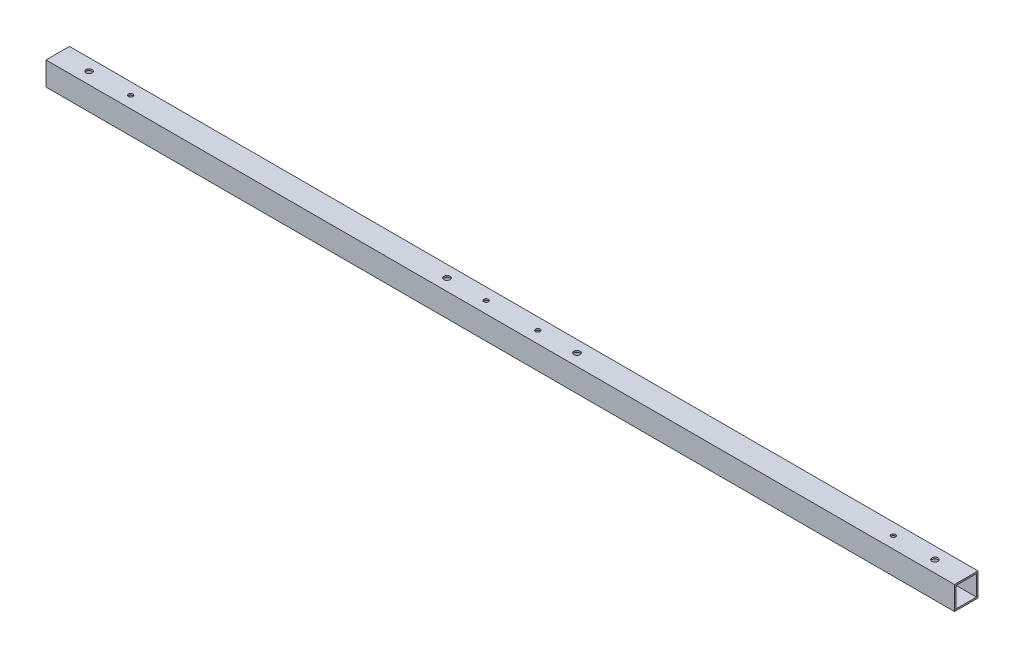
SolidWorks part; units mm, degrees
material "1060 合金"
ref_plane "前视基准面" through (0, 0, 0) normal (0, 0, 1) x (1, 0, 0)
ref_plane "上视基准面" through (0, 0, 0) normal (0, 1, 0) x (1, 0, 0)
ref_plane "右视基准面" through (0, 0, 0) normal (1, 0, 0) x (0, 0, -1)
other "Configuration Table"
sketch "草图1" plane through (0, 0, 0) normal (0, 1, 0) x (1, 0, 0)
  line L0 (-320, 0) -> (320, 0)
  dimension "D1" = 640
other "铝管 15X15X1(1)"
ref_plane "基准面1" through (-320, 0, 0) normal (1, 0, 0) x (0, 0, -1)
sketch "草图11" plane through (-320, 0, 0) normal (1, 0, 0) x (0, 0, -1)
  line L1 (-7.5, -7.5) -> (7.5, -7.5)
  line L2 (-7.5, -7.5) -> (-7.5, 7.5)
  line L3 (-7.5, 7.5) -> (7.5, 7.5)
  line L4 (7.5, -7.5) -> (7.5, 7.5)
  line L5 (-7.5, -7.5) -> (7.5, 7.5) construction
  line L6 (-7.5, 7.5) -> (7.5, -7.5) construction
  line L7 (-6.5, -6.5) -> (6.5, -6.5)
  line L8 (-6.5, -6.5) -> (-6.5, 6.5)
  line L9 (-6.5, 6.5) -> (6.5, 6.5)
  line L10 (6.5, -6.5) -> (6.5, 6.5)
  line L11 (-6.5, -6.5) -> (6.5, 6.5) construction
  line L12 (-6.5, 6.5) -> (6.5, -6.5) construction
  point P0 (0, 0)
  point P6 (0, 0)
  point P11 (0, 0)
  dimension "D1" = 15
  dimension "D2" = 15
  dimension "D3" = 13
  dimension "D4" = 13
sketch "草图12" plane through (0, 7.5, 0) normal (0, 1, 0) x (1, 0, 0)
  line L0 (-320, 0) -> (320, 0) construction
  line L2 (0, 7.5) -> (0, -7.5) construction
  line L3 (320, 7.5) -> (-320, 7.5) construction
  line L4 (320, -7.5) -> (-320, -7.5) construction
  line L5 (-320, 7.5) -> (-320, -7.5) construction
  circle A0 centre (-41.5, 0) radius 1.95
  circle A1 centre (-270, 0) radius 1.95
  circle A2 centre (270, 0) radius 1.95
  circle A3 centre (41.5, 0) radius 1.95
  dimension "D1" = 3.9
  dimension "D2" = 3.9
  dimension "D4" = 41.5
  dimension "D3" = 50
extrude "切除-拉伸1" cut sketch "草图12" against normal through all
sketch "草图13" plane through (0, 7.5, 0) normal (0, 1, 0) x (1, 0, 0)
  line L0 (-320, 0) -> (320, 0) construction
  line L1 (-320, 7.5) -> (-320, -7.5) construction
  line L2 (0, 7.5) -> (0, -9.1662) construction
  line L3 (320, 7.5) -> (-320, 7.5) construction
  circle A0 centre (-243.5, 0) radius 1.45
  circle A1 centre (243.5, 0) radius 1.45
  dimension "D1" = 2.9
  dimension "D2" = 76.5
extrude "切除-拉伸2" cut sketch "草图13" against normal through all
sketch "草图14" plane through (0, 7.5, 0) normal (0, 1, 0) x (1, 0, 0)
  line L0 (0, 7.5) -> (0, -7.5) construction
  line L1 (320, 7.5) -> (-320, 7.5) construction
  line L2 (320, -7.5) -> (-320, -7.5) construction
  line L3 (-320, 0) -> (320, 0) construction
  circle A0 centre (-16.5, 0) radius 1.45
  circle A1 centre (16.5, 0) radius 1.45
  dimension "D1" = 2.9
  dimension "D2" = 2.9
  dimension "D3" = 16.5
  dimension "D4" = 16.5
extrude "切除-拉伸3" cut sketch "草图14" against normal through all
sketch "草图15" plane through (0, 7.5, 0) normal (0, 1, 0) x (1, 0, 0)
  line L0 (-320, 7.5) -> (-320, -7.5) construction
  line L1 (-334.1034, 45.5735) -> (-290, 45.5735)
  line L2 (-334.1034, 45.5735) -> (-334.1034, -30.4523)
  line L3 (-334.1034, -30.4523) -> (-290, -30.4523)
  line L4 (-290, 45.5735) -> (-290, -30.4523)
  line L5 (320.6623, 37.5929) -> (290, 37.5929)
  line L6 (320.6623, 37.5929) -> (320.6623, -43.8933)
  line L7 (320.6623, -43.8933) -> (290, -43.8933)
  line L8 (290, 37.5929) -> (290, -43.8933)
  line L9 (320, 7.5) -> (320, -7.5) construction
  dimension "D1" = 30
  dimension "D2" = 30
extrude "切除-拉伸4" cut sketch "草图15" against normal through all
